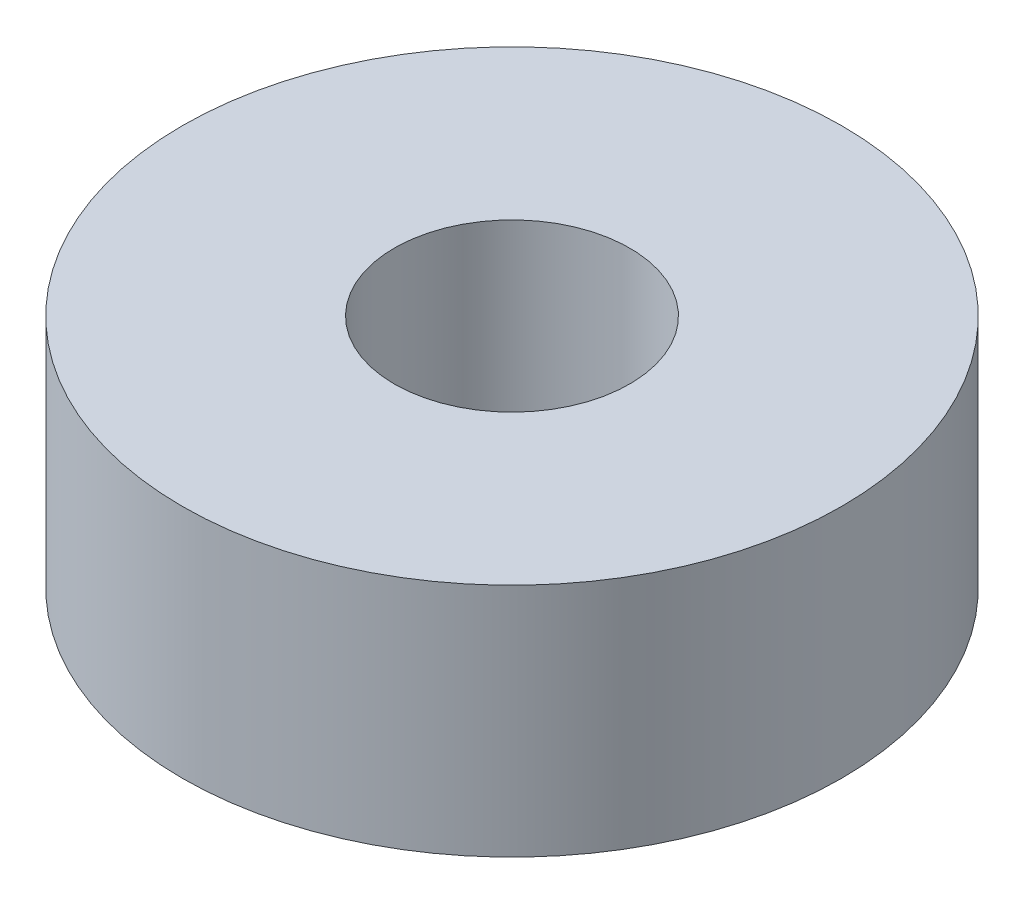
SolidWorks part; units mm, degrees
material "Nickel"
ref_plane "Front Plane" through (0, 0, 0) normal (0, 0, 1) x (1, 0, 0)
ref_plane "Top Plane" through (0, 0, 0) normal (0, 1, 0) x (1, 0, 0)
ref_plane "Right Plane" through (0, 0, 0) normal (1, 0, 0) x (0, 0, -1)
sketch "Sketch1" plane through (0, 0, 0) normal (0, 1, 0) x (1, 0, 0)
  circle A0 centre (0, 0) radius 2.5
  circle A1 centre (0, 0) radius 7
  dimension "D1" = 5
  dimension "D2" = 14
extrude "Boss-Extrude1" add sketch "Sketch1" along normal blind 5
